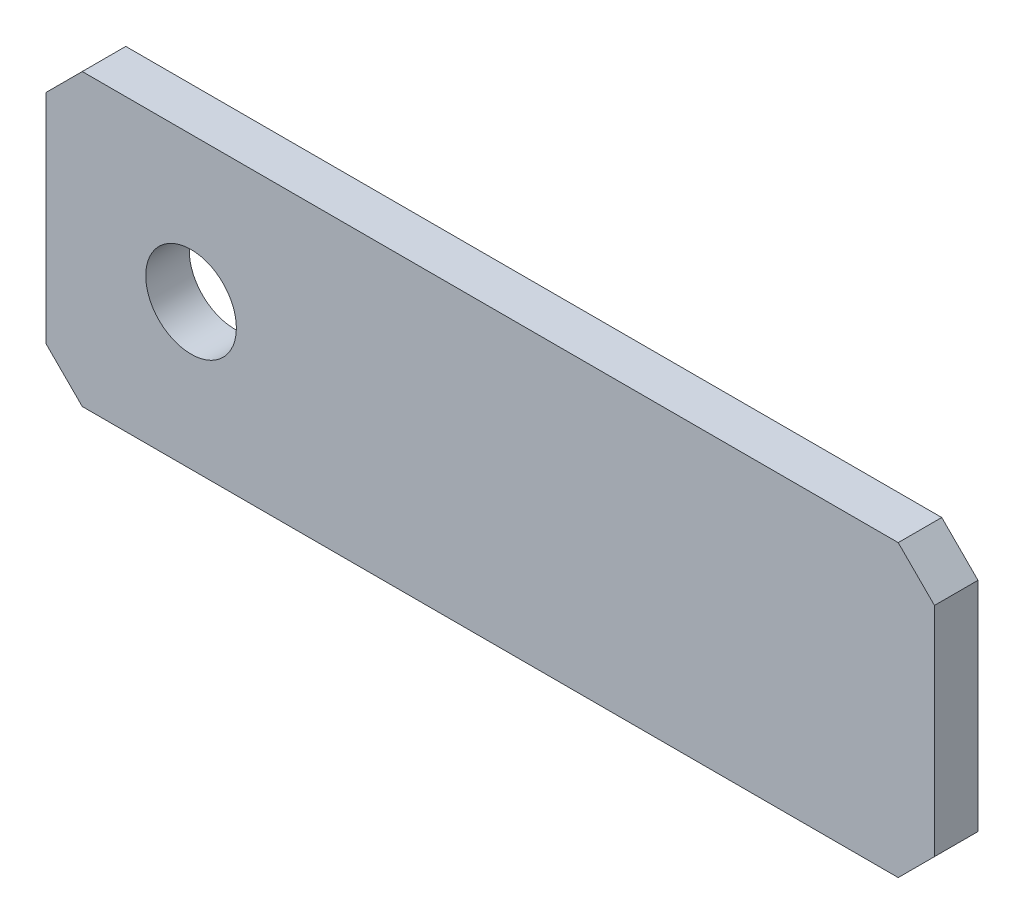
SolidWorks part; units mm, degrees
ref_plane "前视基准面" through (0, 0, 0) normal (0, 0, 1) x (1, 0, 0)
ref_plane "上视基准面" through (0, 0, 0) normal (0, 1, 0) x (1, 0, 0)
ref_plane "右视基准面" through (0, 0, 0) normal (1, 0, 0) x (0, 0, -1)
other "Configuration Table"
sketch "草图_外形24点5乘8_孔位负6_3点5_11点5" plane through (0, 0, 0) normal (0, 0, 1) x (1, 0, 0)
  line L0 (-10, 17.5) -> (-9, 16.5)
  line L1 (-9, 16.5) -> (13.5, 16.5)
  line L2 (13.5, 16.5) -> (14.5, 17.5)
  line L3 (14.5, 17.5) -> (14.5, 23.5)
  line L4 (14.5, 23.5) -> (13.5, 24.5)
  line L5 (13.5, 24.5) -> (-9, 24.5)
  line L6 (-9, 24.5) -> (-10, 23.5)
  line L7 (-10, 23.5) -> (-10, 17.5)
  circle A0 centre (-6, 20.5) radius 1.25
  circle A1 centre (3.5, 20.5) radius 1.1 construction
  circle A2 centre (11.5, 20.5) radius 1.1 construction
  dimension "D1" = 2.5
  dimension "D2" = 2.2
  dimension "D3" = 2.2
extrude "拉伸_板厚1点2_孔贯穿" add sketch "草图_外形24点5乘8_孔位负6_3点5_11点5" along normal blind 1.2
cosmetic thread "M3x0.5_6H_X-6_Y20.5"
sketch "草图_后挡片上下短焊缝_各长8_X3至11_Y16点5和24点5" plane through (0, 0, 0) normal (0, 0, 1) x (1, 0, 0)
  line L0 (3, 16.5) -> (11, 16.5) construction
  line L1 (3, 24.5) -> (11, 24.5) construction
